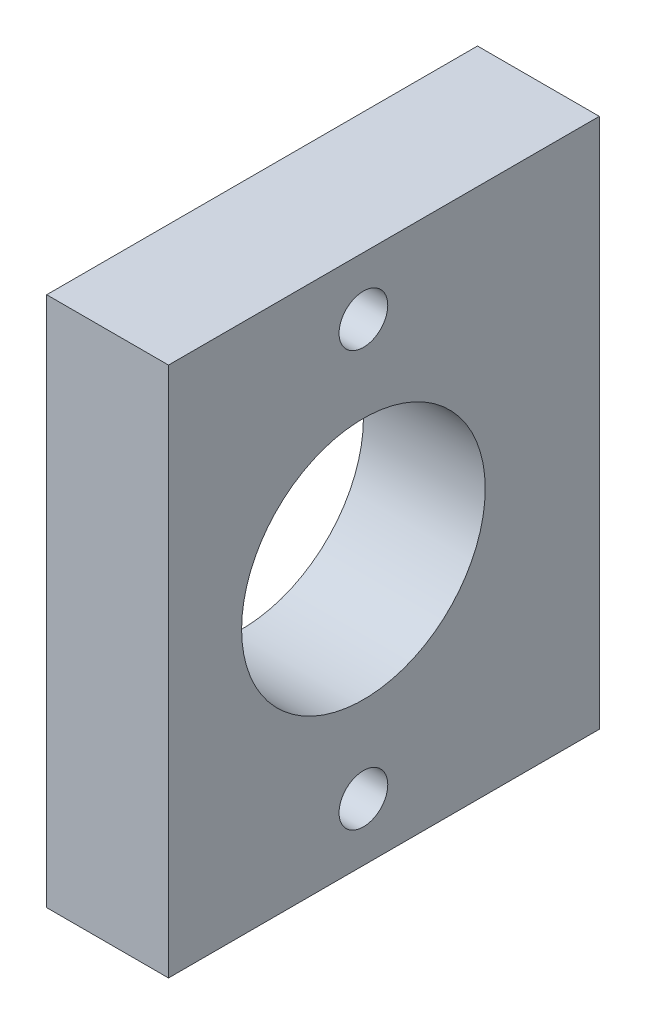
SolidWorks part; units mm, degrees
ref_plane "Front Plane" through (0, 0, 0) normal (0, 0, 1) x (1, 0, 0)
ref_plane "Top Plane" through (0, 0, 0) normal (0, 1, 0) x (1, 0, 0)
ref_plane "Right Plane" through (0, 0, 0) normal (1, 0, 0) x (0, 0, -1)
sketch "Sketch1" plane through (86.0997, 0, 0) normal (1, 0, 0) x (0, 0, -1)
  line L0 (-112.0163, 53.0038) -> (-112.0163, 31.2161)
  line L1 (-112.0163, 31.2161) -> (-94.3336, 31.2161)
  line L2 (-112.0163, 31.2161) -> (-72.5163, 31.2161) construction
  line L3 (-94.3336, 31.2161) -> (-94.3336, 53.0038)
  line L4 (-112.0163, 53.0038) -> (-72.5163, 53.0038) construction
  line L5 (-94.3336, 53.0038) -> (-112.0163, 53.0038)
  line L6 (-104.0163, 33.5878) -> (-94.3336, 42.1099) construction
  line L7 (-94.3336, 42.1099) -> (-104.0163, 50.632) construction
  line L8 (-94.3336, 42.1099) -> (-104.0163, 42.1099) construction
  line L9 (-104.0163, 42.1099) -> (-104.0163, 50.632) construction
  line L10 (-104.0163, 42.1099) -> (-104.0163, 33.5878) construction
  circle A1 centre (-104.0163, 42.1099) radius 5
  circle A2 centre (-104.0163, 50.632) radius 1
  circle A3 centre (-104.0163, 33.5878) radius 1
  dimension "D1" = 2
extrude "Boss-Extrude1" add sketch "Sketch1" along normal blind 5
